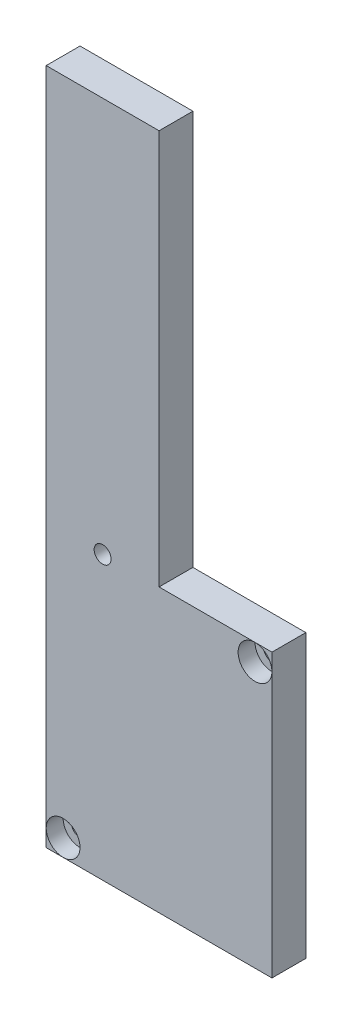
SolidWorks part; units mm, degrees
ref_plane "Plan de face" through (0, 0, 0) normal (0, 0, 1) x (1, 0, 0)
ref_plane "Plan de dessus" through (0, 0, 0) normal (0, 1, 0) x (1, 0, 0)
ref_plane "Plan de droite" through (0, 0, 0) normal (1, 0, 0) x (0, 0, -1)
sketch "Esquisse1" plane through (0, 0, 0) normal (0, 0, 1) x (1, 0, 0)
  line L1 (0, 0) -> (40, 0)
  line L2 (0, 0) -> (0, 120)
  line L3 (0, 120) -> (40, 120)
  line L4 (40, 0) -> (40, 120)
  dimension "D1" = 40
  dimension "D2" = 120
extrude "Boss.-Extru.1" add sketch "Esquisse1" along normal blind 6
sketch "Esquisse2" plane through (0, 0, 6) normal (0, 0, 1) x (1, 0, 0)
  line L1 (40, 120) -> (20, 120)
  line L2 (40, 120) -> (40, 50)
  line L3 (40, 50) -> (20, 50)
  line L4 (20, 120) -> (20, 50)
  dimension "D1" = 70
  dimension "D2" = 20
extrude "Enlèv. mat.-Extru.1" cut sketch "Esquisse2" against normal blind 6
sketch "Esquisse3" plane through (0, 0, 6) normal (0, 0, 1) x (1, 0, 0)
  line L0 (20, 50) -> (40, 50) construction
  line L1 (40, 0) -> (40, 50) construction
  line L2 (0, 0) -> (40, 0) construction
  line L3 (0, 120) -> (0, 0) construction
  circle A0 centre (3, 3) radius 1.5
  circle A1 centre (37, 47) radius 1.5
  dimension "D1" = 3
  dimension "D2" = 3
  dimension "D3" = 3
  dimension "D4" = 3
  dimension "D5" = 3
  dimension "D6" = 3
extrude "Enlèv. mat.-Extru.2" cut sketch "Esquisse3" against normal blind 6
sketch "Esquisse4" plane through (0, 0, 6) normal (0, 0, 1) x (1, 0, 0)
  circle A0 centre (3, 3) radius 2.995
  circle A1 centre (37, 47) radius 2.995
  dimension "D1" = 5.99
  dimension "D2" = 5.99
extrude "Enlèv. mat.-Extru.3" cut sketch "Esquisse4" against normal blind 3
sketch "Esquisse6" plane through (0, 0, 6) normal (0, 0, 1) x (1, 0, 0)
  line L0 (20, 120) -> (20, 50) construction
  line L1 (0, 0) -> (40, 0) construction
  circle A0 centre (10, 50) radius 1.5
  dimension "D1" = 3
  dimension "D3" = 50
  dimension "D2" = 10
extrude "Enlèv. mat.-Extru.4" cut sketch "Esquisse6" against normal blind 6
